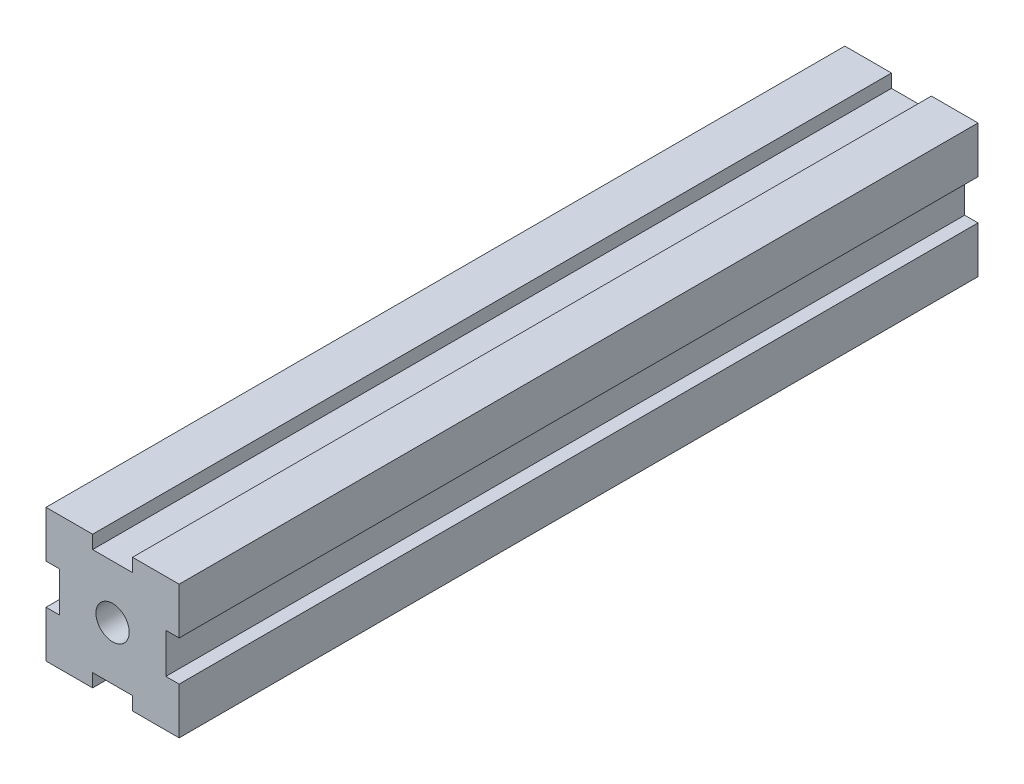
SolidWorks part; units mm, degrees
ref_plane "前视基准面" through (0, 0, 0) normal (0, 0, 1) x (1, 0, 0)
ref_plane "上视基准面" through (0, 0, 0) normal (0, 1, 0) x (1, 0, 0)
ref_plane "右视基准面" through (0, 0, 0) normal (1, 0, 0) x (0, 0, -1)
sketch "草图1" plane through (0, 0, 0) normal (0, 0, 1) x (1, 0, 0)
  line L0 (0, -13) -> (0, -20)
  line L1 (0, 0) -> (7, 0)
  line L2 (0, 0) -> (0, -7)
  line L3 (0, -20) -> (7, -20)
  line L4 (20, 0) -> (20, -7)
  line L5 (20, -7) -> (18, -7)
  line L6 (13, -20) -> (20, -20)
  line L7 (20, -13) -> (18, -13)
  line L8 (18, -7) -> (18, -13)
  line L9 (0, -7) -> (2, -7)
  line L10 (13, 0) -> (20, 0)
  line L11 (0, -13) -> (2, -13)
  line L12 (2, -7) -> (2, -13)
  line L13 (20, -13) -> (20, -20)
  line L14 (7, 0) -> (7, -2)
  line L15 (7, -2) -> (13, -2)
  line L16 (13, 0) -> (13, -2)
  line L17 (0, -7) -> (0, -13) construction
  line L18 (7, -20) -> (7, -18)
  line L19 (7, -18) -> (13, -18)
  line L20 (13, -20) -> (13, -18)
  line L21 (7, 0) -> (13, 0) construction
  line L22 (20, -7) -> (20, -13) construction
  line L23 (13, -20) -> (7, -20) construction
  line L24 (2, -10) -> (18, -10) construction
  line L25 (10, -2) -> (10, -18) construction
  circle A0 centre (10, -10) radius 2.5
  point P21 (10, 0)
  point P22 (10, -2)
  point P23 (10, -18)
  point P24 (2, -10)
  point P25 (18, -10)
  point P26 (0, -10)
  dimension "D13" = 5
  dimension "D1" = 20
  dimension "D2" = 20
  dimension "D3" = 6
  dimension "D4" = 6
  dimension "D5" = 6
  dimension "D6" = 6
  dimension "D7" = 10
  dimension "D8" = 10
  dimension "D9" = 2
  dimension "D10" = 2
  dimension "D11" = 2
  dimension "D12" = 2
extrude "凸台-拉伸1" add sketch "草图1" along normal blind 120
